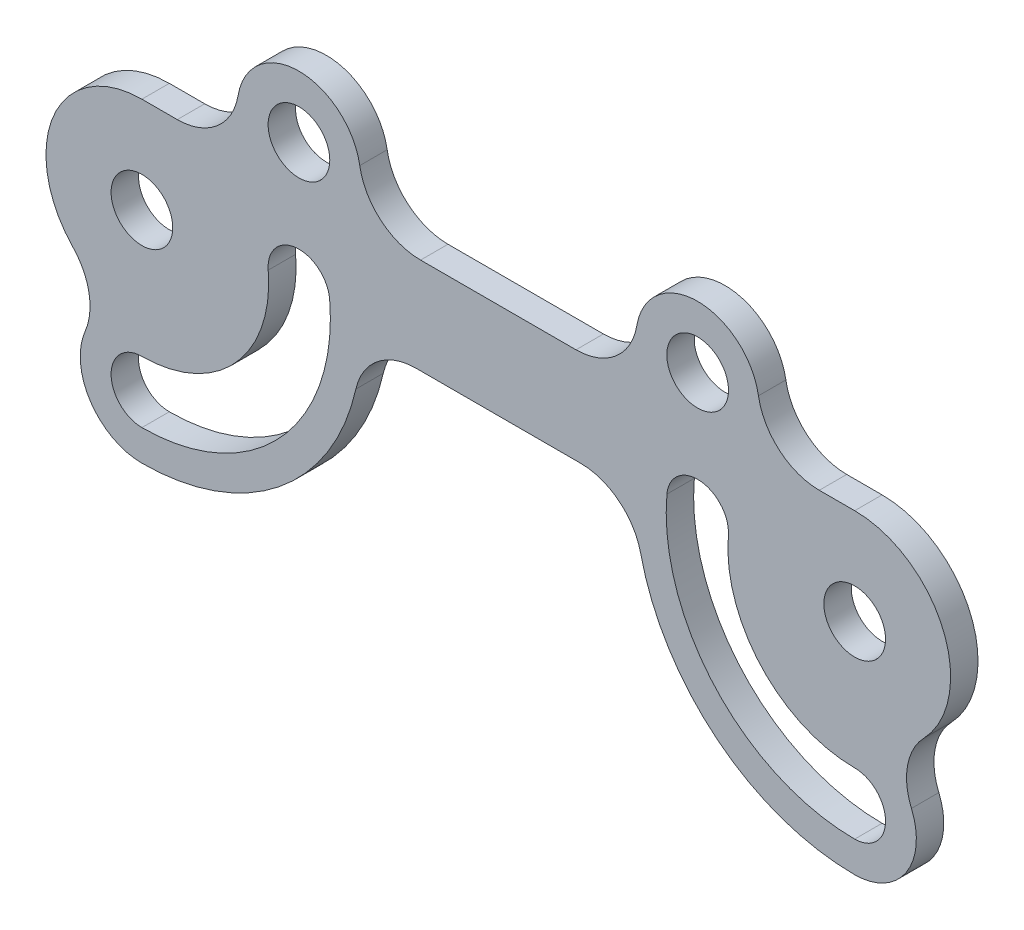
SolidWorks part; units mm, degrees
ref_plane "Front Plane" through (0, 0, 0) normal (0, 0, 1) x (1, 0, 0)
ref_plane "Top Plane" through (0, 0, 0) normal (0, 1, 0) x (1, 0, 0)
ref_plane "Right Plane" through (0, 0, 0) normal (1, 0, 0) x (0, 0, -1)
sketch "Sketch1" plane through (0, 0, 0) normal (0, 0, 1) x (1, 0, 0)
  line L0 (5.5562, 0) -> (35.7188, 0)
  line L1 (0, 5.5562) -> (41.275, 5.5562)
  line L2 (0, 5.5562) -> (0, -5.5562) construction
  line L3 (0, -5.5562) -> (41.275, -5.5562) construction
  line L4 (41.275, 5.5562) -> (41.275, -5.5562) construction
  line L5 (0, 5.5562) -> (41.275, 5.5562) construction
  line L9 (0, 0) -> (9.0934, 0.7956) construction
  line L10 (41.275, 9.1281) -> (41.275, 0) construction
  line L11 (32.1816, 0.7956) -> (30.4025, 0.9512) construction
  line L12 (32.1816, 0.7956) -> (41.275, 0) construction
  line L13 (30.4025, 0.9512) -> (28.6233, 1.1069) construction
  circle A0 centre (0, 0) radius 5.5562 construction
  circle A1 centre (41.275, 0) radius 5.5562 construction
  arc A2 (0, 5.5562) -> (0, -5.5562) centre (0, 0) ccw
  arc A3 (41.275, -5.5562) -> (41.275, 5.5562) centre (41.275, 0) ccw
  circle A4 centre (0, 0) radius 1.7859
  circle A5 centre (41.275, 0) radius 1.7859
  arc A6 (0, -5.5562) -> (5.5562, 0) centre (0, 0) ccw
  arc A7 (35.7188, 0) -> (41.275, -5.5562) centre (41.275, 0) ccw
  circle A16 centre (41.275, -9.1281) radius 1.7859
  circle A20 centre (41.275, -9.1281) radius 3.5719
  circle A21 centre (32.1816, 0.7956) radius 1.7859
  circle A22 centre (32.1816, 0.7956) radius 3.5719 construction
  circle A23 centre (41.275, 0) radius 9.1281 construction
  circle A25 centre (0, 0) radius 9.1281 construction
  circle A40 centre (32.1816, 7.9393) radius 1.7859
  circle A41 centre (32.1816, 7.9393) radius 3.5719
  circle A42 centre (0, -9.1281) radius 3.5719
  circle A46 centre (9.0934, 0.7956) radius 1.7859
  circle A47 centre (9.0934, 7.9393) radius 1.7859
  circle A48 centre (9.0934, 7.9393) radius 3.5719
  circle A49 centre (9.0934, 0.7956) radius 3.5719 construction
  circle A50 centre (0, -9.1281) radius 1.7859
  arc A51 (0, -7.3422) -> (7.3142, 0.6399) centre (0, 0) ccw
  arc A52 (0, -10.9141) -> (10.8725, 0.9512) centre (0, 0) ccw
  arc A53 (0, -12.7) -> (12.6517, 1.1069) centre (0, 0) ccw
  arc A54 (28.6233, 1.1069) -> (41.275, -12.7) centre (41.275, 0) ccw
  arc A55 (30.4025, 0.9512) -> (41.275, -10.9141) centre (41.275, 0) ccw
  arc A56 (33.9608, 0.6399) -> (41.275, -7.3422) centre (41.275, 0) ccw
  dimension "D1" = 41.275
  dimension "D2" = 11.1125
  dimension "D3" = 3.5719
  dimension "D5" = 95
  dimension "D6" = 7.1438
  dimension "D7" = 3.5719
  dimension "D4" = 95
extrude "Boss-Extrude1" add sketch "Sketch1" along normal blind 1.5875
fillet "Fillet1" radius 3.5719 8 edges at (41.275, -5.5562, 0.7937) (29.5209, 5.5562, 0.7937) (34.8423, 5.5562, 0.7937) (6.4327, 5.5562, 0.7937) (11.7541, 5.5562, 0.7937) (12.7, 0, 0.7937) (28.575, 0, 0.7937) (0, -5.5563, 0.7937)
